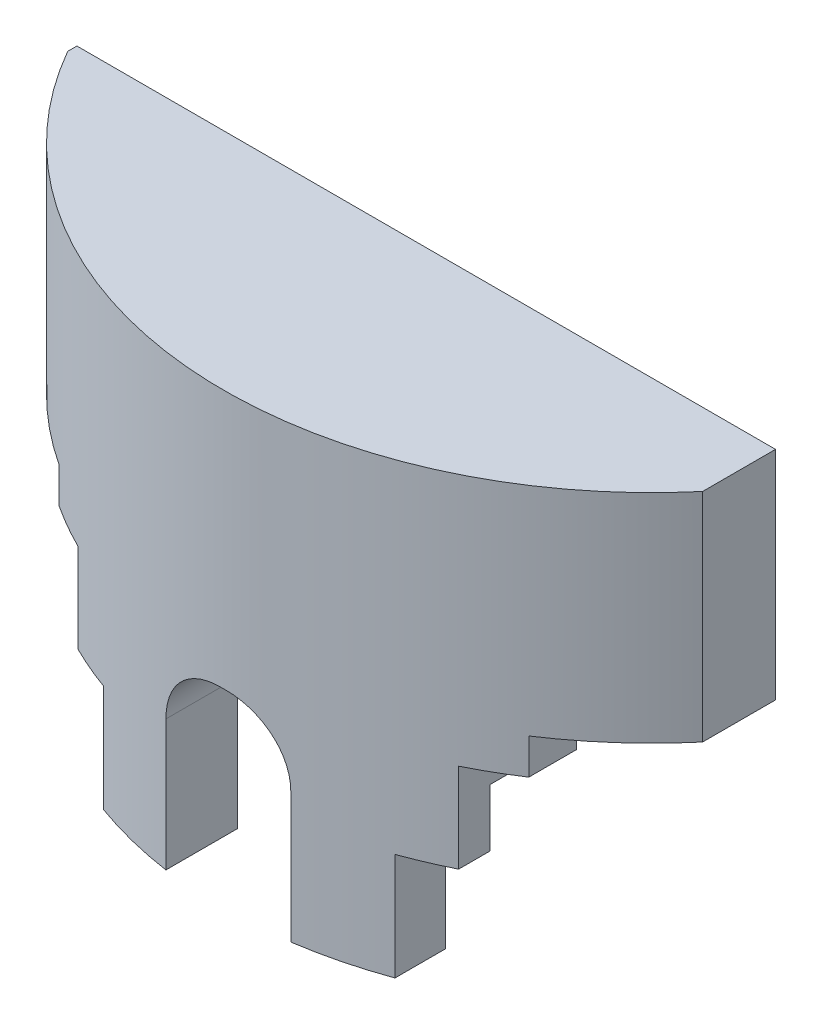
SolidWorks part; units mm, degrees
material "Pure Lead"
ref_plane "Front Plane" through (0, 0, 0) normal (0, 0, 1) x (1, 0, 0)
ref_plane "Top Plane" through (0, 0, 0) normal (0, 1, 0) x (1, 0, 0)
ref_plane "Right Plane" through (0, 0, 0) normal (1, 0, 0) x (0, 0, -1)
sketch "Sketch1" plane through (0, 0, 0) normal (0, 1, 0) x (1, 0, 0)
  line L0 (-62.5, -34.2) -> (-62.5, -35.7456)
  line L1 (-62.5, -34.2) -> (62.5, -34.2)
  line L2 (62.5, -34.2) -> (62.5, -35.7456)
  arc A0 (-62.5, -35.7456) -> (62.5, -35.7456) centre (0, 0) ccw
  dimension "D1" = 144
  dimension "D2" = 125
  dimension "D3" = 34.2
extrude "Boss-Extrude1" add sketch "Sketch1" against normal blind 36.5
sketch "Sketch2" plane through (0, -36.5, 0) normal (0, -1, 0) x (1, 0, 0)
  line L0 (-39.5, 60.1976) -> (-39.5, 34.2)
  line L1 (62.5, 34.2) -> (-62.5, 34.2) construction
  line L2 (-39.5, 34.2) -> (39.5, 34.2)
  line L3 (39.5, 34.2) -> (39.5, 60.1976)
  arc A0 (62.5, 35.7456) -> (-62.5, 35.7456) centre (0, 0) ccw construction
  arc A1 (-39.5, 60.1976) -> (39.5, 60.1976) centre (0, 0) cw
  line M2 (-62.5, 34.2) -> (62.5, 34.2)
  arc M4 (62.5, 35.7456) -> (-62.5, 35.7456) centre (0, 0) ccw
  dimension "D1" = 79
extrude "Boss-Extrude2" add sketch "Sketch2" along normal blind 6 contours L3 L0 M2 M4
sketch "Sketch3" plane through (0, -42.5, 0) normal (0, -1, 0) x (1, 0, 0)
  line L0 (-32, 64.4981) -> (-32, 34.2)
  line L1 (-39.5, 34.2) -> (39.5, 34.2) construction
  line L2 (-32, 34.2) -> (32, 34.2)
  line L3 (32, 34.2) -> (32, 64.4981)
  arc A0 (39.5, 60.1976) -> (-39.5, 60.1976) centre (0, 0) ccw construction
  arc A1 (32, 64.4981) -> (-32, 64.4981) centre (0, 0) ccw
  dimension "D1" = 64
extrude "Boss-Extrude3" add sketch "Sketch3" along normal blind 15
sketch "Sketch4" plane through (0, -57.5, 0) normal (0, -1, 0) x (1, 0, 0)
  line L0 (-24.5, 34.2) -> (-24.5, 67.7034)
  line L1 (-32, 34.2) -> (32, 34.2) construction
  line L2 (-24.5, 34.2) -> (24.5, 34.2)
  line L3 (24.5, 34.2) -> (24.5, 67.7034)
  arc A0 (32, 64.4981) -> (-32, 64.4981) centre (0, 0) ccw construction
  arc A1 (-24.5, 67.7034) -> (24.5, 67.7034) centre (0, 0) cw
  dimension "D1" = 49
extrude "Boss-Extrude4" add sketch "Sketch4" along normal blind 18
sketch "Sketch7" plane through (0, 0, 34.2) normal (0, 0, -1) x (-1, 0, 0)
  line L0 (0, -75.5) -> (0, -53.5) construction
  line L1 (24.5, -75.5) -> (-24.5, -75.5) construction
  line L2 (-32.5, -53.5) -> (-32.5, -86)
  line L3 (-32.5, -86) -> (32.5, -86)
  line L4 (32.5, -86) -> (32.5, -53.5)
  arc A0 (32.5, -53.5) -> (-32.5, -53.5) centre (0, -53.5) ccw
  dimension "D2" = 65
  dimension "D1" = 22
extrude "Cut-Extrude2" cut sketch "Sketch7" against normal blind 25
sketch "Sketch5" plane through (0, -75.5, 0) normal (0, -1, 0) x (1, 0, 0)
  line L0 (-24.5, 34.2) -> (24.5, 34.2) construction
  line L1 (-10.5, 34.2) -> (10.5, 34.2)
  line L2 (-10.5, 34.2) -> (-10.5, 72)
  line L3 (-10.5, 72) -> (10.5, 72)
  line L4 (10.5, 34.2) -> (10.5, 72)
  arc A0 (24.5, 67.7034) -> (-24.5, 67.7034) centre (0, 0) ccw construction
  point P6 (0, 72)
  point P10 (0, 72)
  dimension "D1" = 21
extrude "Cut-Extrude1" cut sketch "Sketch5" against normal blind 32
fillet "Fillet1" radius 10 2 edges at (-10.5, -43.5, 65.2151) (10.5, -43.5, 65.2151)
sketch "Sketch8" plane through (0, 0, 34.2) normal (0, 0, -1) x (-1, 0, 0)
  line L0 (-27, -22) -> (27, -22) construction
  line L1 (-27, -2) -> (27, -2)
  line L2 (-27, -42) -> (27, -42)
  line L3 (-62.5, 0) -> (62.5, 0) construction
  arc A0 (-27, -2) -> (-27, -42) centre (-27, -22) ccw
  arc A1 (27, -42) -> (27, -2) centre (27, -22) ccw
  point P2 (0, -22)
  point P10 (0, 0)
  dimension "D3" = 20
  dimension "D1" = 22
  dimension "D2" = 54
extrude "Cut-Extrude3" cut sketch "Sketch8" against normal blind 18
sketch "Sketch9" plane through (0, 0, 34.2) normal (0, 0, -1) x (-1, 0, 0)
  line L1 (-40.775, -36.5) -> (40.775, -36.5)
  line L2 (-40.775, -36.5) -> (-40.775, -56.5)
  line L3 (-40.775, -56.5) -> (40.775, -56.5)
  line L4 (40.775, -36.5) -> (40.775, -56.5)
  dimension "D1" = 20
extrude "Cut-Extrude4" cut sketch "Sketch9" against normal up to surface (18 mm away) up to face at (0, -27.9799, 52.2)
sketch "Sketch10" plane through (0, 0, 34.2) normal (0, 0, -1) x (-1, 0, 0)
  line L0 (-62.5, 0) -> (62.5, 0) construction
  line L1 (-55, 0) -> (-62.5, 0)
  line L2 (-55, 0) -> (-55, -36.5)
  line L3 (-55, -36.5) -> (-62.5, -36.5)
  line L4 (-62.5, 0) -> (-62.5, -36.5)
  point P7 (0, 0)
  point P8 (0, 0)
  point P9 (-62.5, -36.5)
  dimension "D1" = 55
extrude "Cut-Extrude6" cut sketch "Sketch10" against normal through all
equation "\"smallPulleyTeeth\"= 30"
equation "\"largePulleyTeeth\"= 30"
equation "\"eighthThick\"= 3.0mm"
equation "\"sixteenthThick\" = 1.7mm"
equation "\"quarterThick\"=6.0mm"
equation "\"OD\" = 145mm"
equation "\"puckAngle\" = 60.5deg"
equation "\"puckDiam\" = 76.5mm"
equation "\"puckDist\" = 85mm"
equation "\"scoopFillet\" = 5mm"
equation "\"axlePress\" = 5.9mm"
equation "\"press\" = 0.2mm"
equation "\"wheelClear\" = 0.3mm"
equation "\"10-32clear\" = 4.8mm"
equation "\"10-32tap\" = 4.45mm"
equation "\"6-32clear\" = 3.3mm"
equation "\"8-32clear\" = 4.0mm"
equation "\"4-40clear\" = 3.0mm"
equation "\"wheelHeight\" = 22mm"
equation "\"wheelWell\" = 65mm"
equation "\"ledSmall\" = 3.1mm"
equation "\"ledLarge\" = 4.2mm"
equation "\"ledLength\" = 4.2mm"
equation "\"4-40close\" = 2.7mm"
equation "\"4-40nutThick\" = 2.2mm"
equation "\"4-40nutWidth\" = 6.2mm"
equation "\"4-40insertHeight\" = 3.5mm"
equation "\"4-40insert\" = 4.25mm"
equation "\"D1@Sketch1\"=\"OD\"-1"
